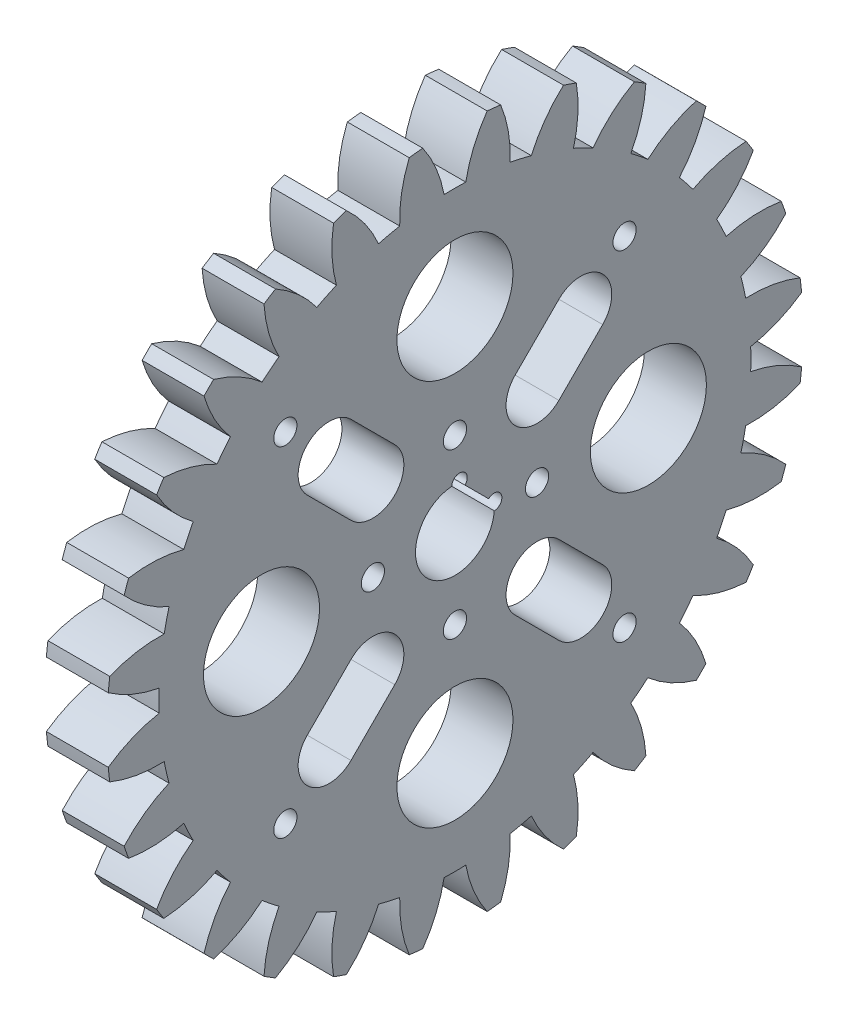
SolidWorks part; units mm, degrees
ref_plane "Front Plane" through (0, 0, 0) normal (0, 0, 1) x (1, 0, 0)
ref_plane "Top Plane" through (0, 0, 0) normal (0, 1, 0) x (1, 0, 0)
ref_plane "Right Plane" through (0, 0, 0) normal (1, 0, 0) x (0, 0, -1)
ref_plane "Plane1" through (4, 0, 0) normal (1, 0, 0) x (0, 0, -1)
sketch "Sketch1" plane through (4, 0, 0) normal (1, 0, 0) x (0, 0, -1)
  circle A0 centre (0, 0) radius 1.5
  arc A1 (-44.8068, 4.1657) -> (-38.2233, 1.4032) centre (-35.1632, 17.9222) ccw
  arc A2 (-38.2233, 1.4032) -> (-38.2233, -1.4032) centre (0, 0) ccw
  arc A3 (-38.2233, -1.4032) -> (-44.8068, -4.1657) centre (-35.1632, -17.9222) ccw
  arc A4 (-44.8068, -4.1657) -> (-44.6103, -5.9092) centre (0, 0) ccw
  arc A5 (-44.6103, -5.9092) -> (-37.5772, -7.1374) centre (-38.2696, 9.6483) ccw
  arc A6 (-37.5772, -7.1374) -> (-36.9527, -9.8735) centre (0, 0) ccw
  arc A7 (-36.9527, -9.8735) -> (-42.7564, -14.0317) centre (-30.2935, -25.2974) ccw
  arc A8 (-42.7564, -14.0317) -> (-42.1769, -15.6878) centre (0, 0) ccw
  arc A9 (-42.1769, -15.6878) -> (-35.0468, -15.3202) centre (-39.457, 0.8906) ccw
  arc A10 (-35.0468, -15.3202) -> (-33.8291, -17.8487) centre (0, 0) ccw
  arc A11 (-33.8291, -17.8487) -> (-38.5621, -23.1941) centre (-23.9048, -31.404) ccw
  arc A12 (-38.5621, -23.1941) -> (-37.6286, -24.6797) centre (0, 0) ccw
  arc A13 (-37.6286, -24.6797) -> (-30.759, -22.7347) centre (-38.6659, -7.9118) ccw
  arc A14 (-30.759, -22.7347) -> (-29.0093, -24.9289) centre (0, 0) ccw
  arc A15 (-29.0093, -24.9289) -> (-32.4341, -31.1934) centre (-16.3174, -35.936) ccw
  arc A16 (-32.4341, -31.1934) -> (-31.1934, -32.4341) centre (0, 0) ccw
  arc A17 (-31.1934, -32.4341) -> (-24.9289, -29.0093) centre (-35.936, -16.3174) ccw
  arc A18 (-24.9289, -29.0093) -> (-22.7347, -30.759) centre (0, 0) ccw
  arc A19 (-22.7347, -30.759) -> (-24.6797, -37.6286) centre (-7.9118, -38.6659) ccw
  arc A20 (-24.6797, -37.6286) -> (-23.1941, -38.5621) centre (0, 0) ccw
  arc A21 (-23.1941, -38.5621) -> (-17.8487, -33.8291) centre (-31.404, -23.9048) ccw
  arc A22 (-17.8487, -33.8291) -> (-15.3202, -35.0468) centre (0, 0) ccw
  arc A23 (-15.3202, -35.0468) -> (-15.6878, -42.1769) centre (0.8906, -39.457) ccw
  arc A24 (-15.6878, -42.1769) -> (-14.0317, -42.7564) centre (0, 0) ccw
  arc A25 (-14.0317, -42.7564) -> (-9.8735, -36.9527) centre (-25.2974, -30.2935) ccw
  arc A26 (-9.8735, -36.9527) -> (-7.1374, -37.5772) centre (0, 0) ccw
  arc A27 (-7.1374, -37.5772) -> (-5.9092, -44.6103) centre (9.6483, -38.2696) ccw
  arc A28 (-5.9092, -44.6103) -> (-4.1657, -44.8068) centre (0, 0) ccw
  arc A29 (-4.1657, -44.8068) -> (-1.4032, -38.2233) centre (-17.9222, -35.1632) ccw
  arc A30 (-1.4032, -38.2233) -> (1.4032, -38.2233) centre (0, 0) ccw
  arc A31 (1.4032, -38.2233) -> (4.1657, -44.8068) centre (17.9222, -35.1632) ccw
  arc A32 (4.1657, -44.8068) -> (5.9092, -44.6103) centre (0, 0) ccw
  arc A33 (5.9092, -44.6103) -> (7.1374, -37.5772) centre (-9.6483, -38.2696) ccw
  arc A34 (7.1374, -37.5772) -> (9.8735, -36.9527) centre (0, 0) ccw
  arc A35 (9.8735, -36.9527) -> (14.0317, -42.7564) centre (25.2974, -30.2935) ccw
  arc A36 (14.0317, -42.7564) -> (15.6878, -42.1769) centre (0, 0) ccw
  arc A37 (15.6878, -42.1769) -> (15.3202, -35.0468) centre (-0.8906, -39.457) ccw
  arc A38 (15.3202, -35.0468) -> (17.8487, -33.8291) centre (0, 0) ccw
  arc A39 (17.8487, -33.8291) -> (23.1941, -38.5621) centre (31.404, -23.9048) ccw
  arc A40 (23.1941, -38.5621) -> (24.6797, -37.6286) centre (0, 0) ccw
  arc A41 (24.6797, -37.6286) -> (22.7347, -30.759) centre (7.9118, -38.6659) ccw
  arc A42 (22.7347, -30.759) -> (24.9289, -29.0093) centre (0, 0) ccw
  arc A43 (24.9289, -29.0093) -> (31.1934, -32.4341) centre (35.936, -16.3174) ccw
  arc A44 (31.1934, -32.4341) -> (32.4341, -31.1934) centre (0, 0) ccw
  arc A45 (32.4341, -31.1934) -> (29.0093, -24.9289) centre (16.3174, -35.936) ccw
  arc A46 (29.0093, -24.9289) -> (30.759, -22.7347) centre (0, 0) ccw
  arc A47 (30.759, -22.7347) -> (37.6286, -24.6797) centre (38.6659, -7.9118) ccw
  arc A48 (37.6286, -24.6797) -> (38.5621, -23.1941) centre (0, 0) ccw
  arc A49 (38.5621, -23.1941) -> (33.8291, -17.8487) centre (23.9048, -31.404) ccw
  arc A50 (33.8291, -17.8487) -> (35.0468, -15.3202) centre (0, 0) ccw
  arc A51 (35.0468, -15.3202) -> (42.1769, -15.6878) centre (39.457, 0.8906) ccw
  arc A52 (42.1769, -15.6878) -> (42.7564, -14.0317) centre (0, 0) ccw
  arc A53 (42.7564, -14.0317) -> (36.9527, -9.8735) centre (30.2935, -25.2974) ccw
  arc A54 (36.9527, -9.8735) -> (37.5772, -7.1374) centre (0, 0) ccw
  arc A55 (37.5772, -7.1374) -> (44.6103, -5.9092) centre (38.2696, 9.6483) ccw
  arc A56 (44.6103, -5.9092) -> (44.8068, -4.1657) centre (0, 0) ccw
  arc A57 (44.8068, -4.1657) -> (38.2233, -1.4032) centre (35.1632, -17.9222) ccw
  arc A58 (38.2233, -1.4032) -> (38.2233, 1.4032) centre (0, 0) ccw
  arc A59 (38.2233, 1.4032) -> (44.8068, 4.1657) centre (35.1632, 17.9222) ccw
  arc A60 (44.8068, 4.1657) -> (44.6103, 5.9092) centre (0, 0) ccw
  arc A61 (44.6103, 5.9092) -> (37.5772, 7.1374) centre (38.2696, -9.6483) ccw
  arc A62 (37.5772, 7.1374) -> (36.9527, 9.8735) centre (0, 0) ccw
  arc A63 (36.9527, 9.8735) -> (42.7564, 14.0317) centre (30.2935, 25.2974) ccw
  arc A64 (42.7564, 14.0317) -> (42.1769, 15.6878) centre (0, 0) ccw
  arc A65 (42.1769, 15.6878) -> (35.0468, 15.3202) centre (39.457, -0.8906) ccw
  arc A66 (35.0468, 15.3202) -> (33.8291, 17.8487) centre (0, 0) ccw
  arc A67 (33.8291, 17.8487) -> (38.5621, 23.1941) centre (23.9048, 31.404) ccw
  arc A68 (38.5621, 23.1941) -> (37.6286, 24.6797) centre (0, 0) ccw
  arc A69 (37.6286, 24.6797) -> (30.759, 22.7347) centre (38.6659, 7.9118) ccw
  arc A70 (30.759, 22.7347) -> (29.0093, 24.9289) centre (0, 0) ccw
  arc A71 (29.0093, 24.9289) -> (32.4341, 31.1934) centre (16.3174, 35.936) ccw
  arc A72 (32.4341, 31.1934) -> (31.1934, 32.4341) centre (0, 0) ccw
  arc A73 (31.1934, 32.4341) -> (24.9289, 29.0093) centre (35.936, 16.3174) ccw
  arc A74 (24.9289, 29.0093) -> (22.7347, 30.759) centre (0, 0) ccw
  arc A75 (22.7347, 30.759) -> (24.6797, 37.6286) centre (7.9118, 38.6659) ccw
  arc A76 (24.6797, 37.6286) -> (23.1941, 38.5621) centre (0, 0) ccw
  arc A77 (23.1941, 38.5621) -> (17.8487, 33.8291) centre (31.404, 23.9048) ccw
  arc A78 (17.8487, 33.8291) -> (15.3202, 35.0468) centre (0, 0) ccw
  arc A79 (15.3202, 35.0468) -> (15.6878, 42.1769) centre (-0.8906, 39.457) ccw
  arc A80 (15.6878, 42.1769) -> (14.0317, 42.7564) centre (0, 0) ccw
  arc A81 (14.0317, 42.7564) -> (9.8735, 36.9527) centre (25.2974, 30.2935) ccw
  arc A82 (9.8735, 36.9527) -> (7.1374, 37.5772) centre (0, 0) ccw
  arc A83 (7.1374, 37.5772) -> (5.9092, 44.6103) centre (-9.6483, 38.2696) ccw
  arc A84 (5.9092, 44.6103) -> (4.1657, 44.8068) centre (0, 0) ccw
  arc A85 (4.1657, 44.8068) -> (1.4032, 38.2233) centre (17.9222, 35.1632) ccw
  arc A86 (1.4032, 38.2233) -> (-1.4032, 38.2233) centre (0, 0) ccw
  arc A87 (-1.4032, 38.2233) -> (-4.1657, 44.8068) centre (-17.9222, 35.1632) ccw
  arc A88 (-4.1657, 44.8068) -> (-5.9092, 44.6103) centre (0, 0) ccw
  arc A89 (-5.9092, 44.6103) -> (-7.1374, 37.5772) centre (9.6483, 38.2696) ccw
  arc A90 (-7.1374, 37.5772) -> (-9.8735, 36.9527) centre (0, 0) ccw
  arc A91 (-9.8735, 36.9527) -> (-14.0317, 42.7564) centre (-25.2974, 30.2935) ccw
  arc A92 (-14.0317, 42.7564) -> (-15.6878, 42.1769) centre (0, 0) ccw
  arc A93 (-15.6878, 42.1769) -> (-15.3202, 35.0468) centre (0.8906, 39.457) ccw
  arc A94 (-15.3202, 35.0468) -> (-17.8487, 33.8291) centre (0, 0) ccw
  arc A95 (-17.8487, 33.8291) -> (-23.1941, 38.5621) centre (-31.404, 23.9048) ccw
  arc A96 (-23.1941, 38.5621) -> (-24.6797, 37.6286) centre (0, 0) ccw
  arc A97 (-24.6797, 37.6286) -> (-22.7347, 30.759) centre (-7.9118, 38.6659) ccw
  arc A98 (-22.7347, 30.759) -> (-24.9289, 29.0093) centre (0, 0) ccw
  arc A99 (-24.9289, 29.0093) -> (-31.1934, 32.4341) centre (-35.936, 16.3174) ccw
  arc A100 (-31.1934, 32.4341) -> (-32.4341, 31.1934) centre (0, 0) ccw
  arc A101 (-32.4341, 31.1934) -> (-29.0093, 24.9289) centre (-16.3174, 35.936) ccw
  arc A102 (-29.0093, 24.9289) -> (-30.759, 22.7347) centre (0, 0) ccw
  arc A103 (-30.759, 22.7347) -> (-37.6286, 24.6797) centre (-38.6659, 7.9118) ccw
  arc A104 (-37.6286, 24.6797) -> (-38.5621, 23.1941) centre (0, 0) ccw
  arc A105 (-38.5621, 23.1941) -> (-33.8291, 17.8487) centre (-23.9048, 31.404) ccw
  arc A106 (-33.8291, 17.8487) -> (-35.0468, 15.3202) centre (0, 0) ccw
  arc A107 (-35.0468, 15.3202) -> (-42.1769, 15.6878) centre (-39.457, -0.8906) ccw
  arc A108 (-42.1769, 15.6878) -> (-42.7564, 14.0317) centre (0, 0) ccw
  arc A109 (-42.7564, 14.0317) -> (-36.9527, 9.8735) centre (-30.2935, 25.2974) ccw
  arc A110 (-36.9527, 9.8735) -> (-37.5772, 7.1374) centre (0, 0) ccw
  arc A111 (-37.5772, 7.1374) -> (-44.6103, 5.9092) centre (-38.2696, -9.6483) ccw
  arc A112 (-44.6103, 5.9092) -> (-44.8068, 4.1657) centre (0, 0) ccw
extrude "Boss-Extrude1" add sketch "Sketch1" against normal blind 4
sketch "Sketch2" plane through (4, 0, 0) normal (1, 0, 0) x (0, 0, -1)
  line L0 (5.0656, 0.5912) -> (0.5912, 5.0656)
  circle A0 centre (0, 10.6066) radius 1.5
  arc A1 (0.5912, 5.0656) -> (5.0656, 0.5912) centre (0, 0) ccw
  circle A2 centre (10.6066, 0) radius 1.5
  circle A3 centre (0, -10.6066) radius 1.5
  circle A4 centre (-10.6066, 0) radius 1.5
extrude "Cut-Extrude1" cut sketch "Sketch2" against normal through all
sketch "Sketch3" plane through (4, 0, 0) normal (1, 0, 0) x (0, 0, -1)
  line L0 (-13.435, 19.0919) -> (-7.7782, 13.435)
  line L1 (-19.0919, 13.435) -> (-13.435, 7.7782)
  line L2 (19.0919, 13.435) -> (13.435, 7.7782)
  line L3 (13.435, 19.0919) -> (7.7782, 13.435)
  line L4 (13.435, -19.0919) -> (7.7782, -13.435)
  line L5 (19.0919, -13.435) -> (13.435, -7.7782)
  line L6 (-19.0919, -13.435) -> (-13.435, -7.7782)
  line L7 (-13.435, -19.0919) -> (-7.7782, -13.435)
  circle A0 centre (-21.9203, 21.9203) radius 1.5
  circle A1 centre (0, 25) radius 7.5
  circle A2 centre (25, 0) radius 7.5
  circle A3 centre (21.9203, 21.9203) radius 1.5
  circle A4 centre (0, -25) radius 7.5
  circle A5 centre (21.9203, -21.9203) radius 1.5
  circle A6 centre (-25, 0) radius 7.5
  circle A7 centre (-21.9203, -21.9203) radius 1.5
  arc A8 (-13.435, 19.0919) -> (-19.0919, 13.435) centre (-16.2635, 16.2635) ccw
  arc A9 (-13.435, 7.7782) -> (-7.7782, 13.435) centre (-10.6066, 10.6066) ccw
  arc A10 (19.0919, 13.435) -> (13.435, 19.0919) centre (16.2635, 16.2635) ccw
  arc A11 (7.7782, 13.435) -> (13.435, 7.7782) centre (10.6066, 10.6066) ccw
  arc A12 (13.435, -19.0919) -> (19.0919, -13.435) centre (16.2635, -16.2635) ccw
  arc A13 (13.435, -7.7782) -> (7.7782, -13.435) centre (10.6066, -10.6066) ccw
  arc A14 (-19.0919, -13.435) -> (-13.435, -19.0919) centre (-16.2635, -16.2635) ccw
  arc A15 (-7.7782, -13.435) -> (-13.435, -7.7782) centre (-10.6066, -10.6066) ccw
  circle A16 centre (0.5912, 5.0656) radius 1
  circle A17 centre (5.0656, 0.5912) radius 1
extrude "Cut-Extrude2" cut sketch "Sketch3" against normal through all
other "Move Face1" face at (4, -21.9203, -23.4203) parameters "D1"=4
